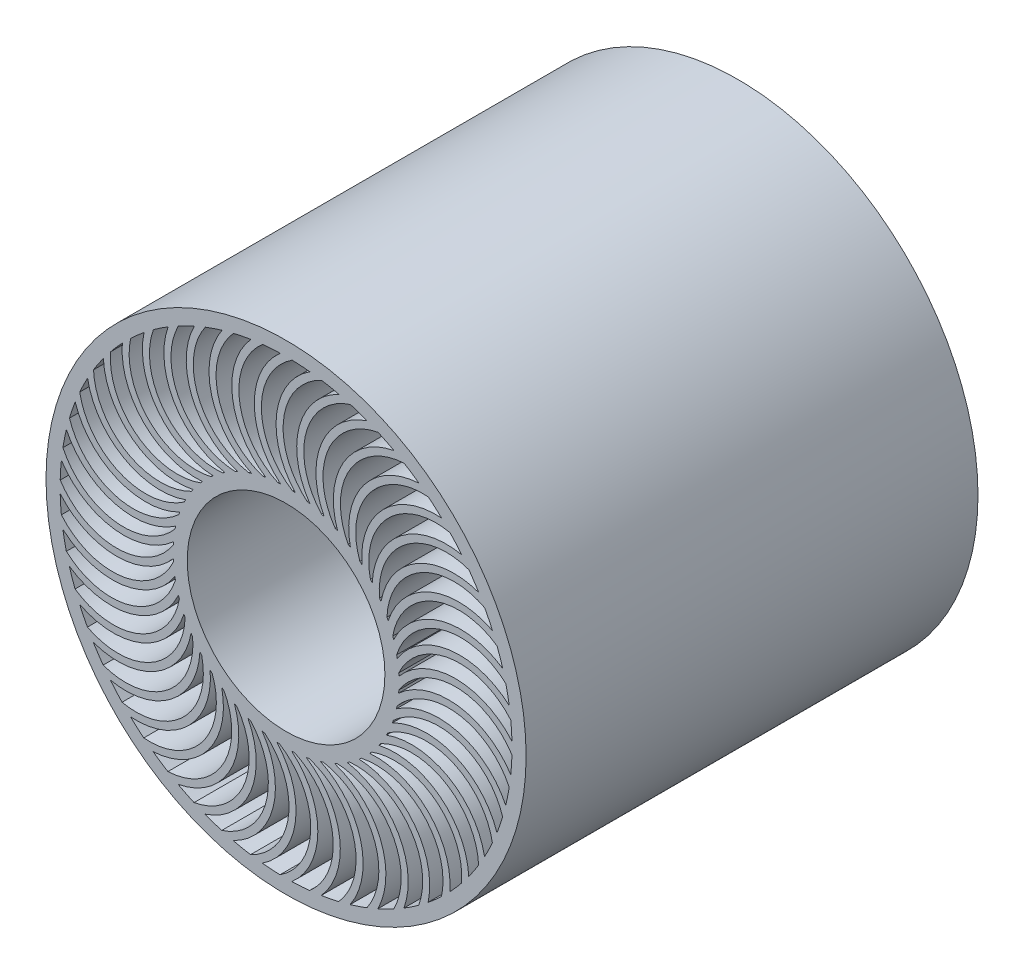
SolidWorks part; units mm, degrees
material "POLYURETHANE (11671)"
ref_plane "Front Plane" through (0, 0, 0) normal (0, 0, 1) x (1, 0, 0)
ref_plane "Top Plane" through (0, 0, 0) normal (0, 1, 0) x (1, 0, 0)
ref_plane "Right Plane" through (0, 0, 0) normal (1, 0, 0) x (0, 0, -1)
sketch "Sketch1" plane through (0, 0, 0) normal (0, 0, 1) x (1, 0, 0)
  line L0 (0, 50.8) -> (0, 101.6)
  line L1 (0, 101.6) -> (99.4973, 101.6) construction
  line L4 (1.5875, 47.8017) -> (1.5875, 104.5983) construction
  line L5 (1.5875, 101.5876) -> (1.5875, 101.6)
  line L6 (-1.5875, 54.2032) -> (-1.5875, 98.1968) construction
  circle A1 centre (0, 0) radius 107.95
  circle A2 centre (0, 0) radius 101.6
  circle A3 centre (0, 0) radius 12.7
  circle A4 centre (0, 0) radius 50.8
  arc A5 (0, 50.8) -> (0, 101.6) centre (19.0524, 76.2) cw construction
  arc A6 (-2.4712, 50.7399) -> (-2.5807, 101.5672) centre (19.0524, 76.2) cw
  arc A7 (2.914, 50.7164) -> (2.7257, 101.5634) centre (19.0524, 76.2) cw
  arc A8 (1.5875, 47.8017) -> (1.5875, 104.5983) centre (19.0524, 76.2) cw construction
  arc A9 (-1.5875, 54.2032) -> (-1.5875, 98.1968) centre (19.0524, 76.2) cw construction
  arc A10 (4.1728, 50.6283) -> (10.6986, 101.0351) centre (28.8355, 73.0613) cw
  arc A11 (9.5089, 49.9021) -> (15.9591, 100.3388) centre (28.8355, 73.0613) cw
  circle A12 centre (0, 0) radius 50.8
  arc A13 (10.7454, 49.6505) -> (23.7948, 98.7743) centre (38.1252, 68.6724) cw
  arc A14 (15.9411, 48.234) -> (28.9194, 97.3973) centre (38.1252, 68.6724) cw
  circle A15 centre (0, 0) radius 50.8
  arc A16 (17.1342, 47.8232) -> (36.4839, 94.8235) centre (46.7626, 63.1086) cw
  arc A17 (22.1005, 45.7406) -> (41.3849, 92.7893) centre (46.7626, 63.1086) cw
  circle A18 centre (0, 0) radius 50.8
  arc A19 (23.2298, 45.1776) -> (48.5487, 89.2501) centre (54.5999, 56.4649) cw
  arc A20 (27.8818, 42.4646) -> (53.1423, 86.5936) centre (54.5999, 56.4649) cw
  circle A21 centre (0, 0) radius 50.8
  arc A22 (28.9279, 41.759) -> (59.7828, 82.1497) centre (61.5029, 48.8552) cw
  arc A23 (33.186, 38.462) -> (63.9904, 78.9164) centre (61.5029, 48.8552) cw
  circle A24 centre (0, 0) radius 50.8
  arc A25 (34.1311, 37.6259) -> (69.9941, 73.6437) centre (67.3536, 40.4095) cw
  arc A26 (37.9224, 33.8013) -> (73.7436, 69.8888) centre (67.3536, 40.4095) cw
  circle A27 centre (0, 0) radius 50.8
  arc A28 (38.7503, 32.849) -> (79.0077, 63.8776) centre (72.0519, 31.2723) cw
  arc A29 (42.0099, 28.5623) -> (82.235, 59.6654) centre (72.0519, 31.2723) cw
  circle A30 centre (0, 0) radius 50.8
  arc A31 (42.7064, 27.5101) -> (86.6695, 53.0185) centre (75.5173, 21.6001) cw
  arc A32 (45.3787, 22.8346) -> (89.3194, 48.4212) centre (75.5173, 21.6001) cw
  circle A33 centre (0, 0) radius 50.8
  arc A34 (45.9318, 21.7004) -> (92.8483, 41.2523) centre (77.6907, 11.5584) cw
  arc A35 (47.971, 16.7161) -> (94.8755, 36.3484) centre (77.6907, 11.5584) cw
  circle A36 centre (0, 0) radius 50.8
  arc A37 (48.3713, 15.5195) -> (97.4385, 28.7803) centre (78.5347, 1.3188) cw
  arc A38 (49.7424, 10.3116) -> (98.8082, 23.6537) centre (78.5347, 1.3188) cw
  circle A39 centre (0, 0) radius 50.8
  arc A40 (49.9832, 9.073) -> (100.3615, 15.8158) centre (78.0349, -8.9433) cw
  arc A41 (50.6628, 3.7307) -> (101.0503, 10.5543) centre (78.0349, -8.9433) cw
  circle A42 centre (0, 0) radius 50.8
  arc A43 (50.7399, 2.4712) -> (101.5672, 2.5807) centre (76.2, -19.0524) cw
  arc A44 (50.7164, -2.914) -> (101.5634, -2.7257) centre (76.2, -19.0524) cw
  circle A45 centre (0, 0) radius 50.8
  arc A46 (50.6283, -4.1728) -> (101.0351, -10.6986) centre (73.0613, -28.8355) cw
  arc A47 (49.9021, -9.5089) -> (100.3388, -15.9591) centre (73.0613, -28.8355) cw
  circle A48 centre (0, 0) radius 50.8
  arc A49 (49.6505, -10.7454) -> (98.7743, -23.7948) centre (68.6724, -38.1252) cw
  arc A50 (48.234, -15.9411) -> (97.3973, -28.9194) centre (68.6724, -38.1252) cw
  circle A51 centre (0, 0) radius 50.8
  arc A52 (47.8232, -17.1342) -> (94.8235, -36.4839) centre (63.1086, -46.7626) cw
  arc A53 (45.7406, -22.1005) -> (92.7893, -41.3849) centre (63.1086, -46.7626) cw
  circle A54 centre (0, 0) radius 50.8
  arc A55 (45.1776, -23.2298) -> (89.2501, -48.5487) centre (56.4649, -54.5999) cw
  arc A56 (42.4646, -27.8818) -> (86.5936, -53.1423) centre (56.4649, -54.5999) cw
  circle A57 centre (0, 0) radius 50.8
  arc A58 (41.759, -28.9279) -> (82.1497, -59.7828) centre (48.8552, -61.5029) cw
  arc A59 (38.462, -33.186) -> (78.9164, -63.9904) centre (48.8552, -61.5029) cw
  circle A60 centre (0, 0) radius 50.8
  arc A61 (37.6259, -34.1311) -> (73.6437, -69.9941) centre (40.4095, -67.3536) cw
  arc A62 (33.8013, -37.9224) -> (69.8888, -73.7436) centre (40.4095, -67.3536) cw
  circle A63 centre (0, 0) radius 50.8
  arc A64 (32.849, -38.7503) -> (63.8776, -79.0077) centre (31.2723, -72.0519) cw
  arc A65 (28.5623, -42.0099) -> (59.6654, -82.235) centre (31.2723, -72.0519) cw
  circle A66 centre (0, 0) radius 50.8
  arc A67 (27.5101, -42.7064) -> (53.0185, -86.6695) centre (21.6001, -75.5173) cw
  arc A68 (22.8346, -45.3787) -> (48.4212, -89.3194) centre (21.6001, -75.5173) cw
  circle A69 centre (0, 0) radius 50.8
  arc A70 (21.7004, -45.9318) -> (41.2523, -92.8483) centre (11.5584, -77.6907) cw
  arc A71 (16.7161, -47.971) -> (36.3484, -94.8755) centre (11.5584, -77.6907) cw
  circle A72 centre (0, 0) radius 50.8
  arc A73 (15.5195, -48.3713) -> (28.7803, -97.4385) centre (1.3188, -78.5347) cw
  arc A74 (10.3116, -49.7424) -> (23.6537, -98.8082) centre (1.3188, -78.5347) cw
  circle A75 centre (0, 0) radius 50.8
  arc A76 (9.073, -49.9832) -> (15.8158, -100.3615) centre (-8.9433, -78.0349) cw
  arc A77 (3.7307, -50.6628) -> (10.5543, -101.0503) centre (-8.9433, -78.0349) cw
  circle A78 centre (0, 0) radius 50.8
  arc A79 (2.4712, -50.7399) -> (2.5807, -101.5672) centre (-19.0524, -76.2) cw
  arc A80 (-2.914, -50.7164) -> (-2.7257, -101.5634) centre (-19.0524, -76.2) cw
  circle A81 centre (0, 0) radius 50.8
  arc A82 (-4.1728, -50.6283) -> (-10.6986, -101.0351) centre (-28.8355, -73.0613) cw
  arc A83 (-9.5089, -49.9021) -> (-15.9591, -100.3388) centre (-28.8355, -73.0613) cw
  circle A84 centre (0, 0) radius 50.8
  arc A85 (-10.7454, -49.6505) -> (-23.7948, -98.7743) centre (-38.1252, -68.6724) cw
  arc A86 (-15.9411, -48.234) -> (-28.9194, -97.3973) centre (-38.1252, -68.6724) cw
  circle A87 centre (0, 0) radius 50.8
  arc A88 (-17.1342, -47.8232) -> (-36.4839, -94.8235) centre (-46.7626, -63.1086) cw
  arc A89 (-22.1005, -45.7406) -> (-41.3849, -92.7893) centre (-46.7626, -63.1086) cw
  circle A90 centre (0, 0) radius 50.8
  arc A91 (-23.2298, -45.1776) -> (-48.5487, -89.2501) centre (-54.5999, -56.4649) cw
  arc A92 (-27.8818, -42.4646) -> (-53.1423, -86.5936) centre (-54.5999, -56.4649) cw
  circle A93 centre (0, 0) radius 50.8
  arc A94 (-28.9279, -41.759) -> (-59.7828, -82.1497) centre (-61.5029, -48.8552) cw
  arc A95 (-33.186, -38.462) -> (-63.9904, -78.9164) centre (-61.5029, -48.8552) cw
  circle A96 centre (0, 0) radius 50.8
  arc A97 (-34.1311, -37.6259) -> (-69.9941, -73.6437) centre (-67.3536, -40.4095) cw
  arc A98 (-37.9224, -33.8013) -> (-73.7436, -69.8888) centre (-67.3536, -40.4095) cw
  circle A99 centre (0, 0) radius 50.8
  arc A100 (-38.7503, -32.849) -> (-79.0077, -63.8776) centre (-72.0519, -31.2723) cw
  arc A101 (-42.0099, -28.5623) -> (-82.235, -59.6654) centre (-72.0519, -31.2723) cw
  circle A102 centre (0, 0) radius 50.8
  arc A103 (-42.7064, -27.5101) -> (-86.6695, -53.0185) centre (-75.5173, -21.6001) cw
  arc A104 (-45.3787, -22.8346) -> (-89.3194, -48.4212) centre (-75.5173, -21.6001) cw
  circle A105 centre (0, 0) radius 50.8
  arc A106 (-45.9318, -21.7004) -> (-92.8483, -41.2523) centre (-77.6907, -11.5584) cw
  arc A107 (-47.971, -16.7161) -> (-94.8755, -36.3484) centre (-77.6907, -11.5584) cw
  circle A108 centre (0, 0) radius 50.8
  arc A109 (-48.3713, -15.5195) -> (-97.4385, -28.7803) centre (-78.5347, -1.3188) cw
  arc A110 (-49.7424, -10.3116) -> (-98.8082, -23.6537) centre (-78.5347, -1.3188) cw
  circle A111 centre (0, 0) radius 50.8
  arc A112 (-49.9832, -9.073) -> (-100.3615, -15.8158) centre (-78.0349, 8.9433) cw
  arc A113 (-50.6628, -3.7307) -> (-101.0503, -10.5543) centre (-78.0349, 8.9433) cw
  circle A114 centre (0, 0) radius 50.8
  arc A115 (-50.7399, -2.4712) -> (-101.5672, -2.5807) centre (-76.2, 19.0524) cw
  arc A116 (-50.7164, 2.914) -> (-101.5634, 2.7257) centre (-76.2, 19.0524) cw
  circle A117 centre (0, 0) radius 50.8
  arc A118 (-50.6283, 4.1728) -> (-101.0351, 10.6986) centre (-73.0613, 28.8355) cw
  arc A119 (-49.9021, 9.5089) -> (-100.3388, 15.9591) centre (-73.0613, 28.8355) cw
  circle A120 centre (0, 0) radius 50.8
  arc A121 (-49.6505, 10.7454) -> (-98.7743, 23.7948) centre (-68.6724, 38.1252) cw
  arc A122 (-48.234, 15.9411) -> (-97.3973, 28.9194) centre (-68.6724, 38.1252) cw
  circle A123 centre (0, 0) radius 50.8
  arc A124 (-47.8232, 17.1342) -> (-94.8235, 36.4839) centre (-63.1086, 46.7626) cw
  arc A125 (-45.7406, 22.1005) -> (-92.7893, 41.3849) centre (-63.1086, 46.7626) cw
  circle A126 centre (0, 0) radius 50.8
  arc A127 (-45.1776, 23.2298) -> (-89.2501, 48.5487) centre (-56.4649, 54.5999) cw
  arc A128 (-42.4646, 27.8818) -> (-86.5936, 53.1423) centre (-56.4649, 54.5999) cw
  circle A129 centre (0, 0) radius 50.8
  arc A130 (-41.759, 28.9279) -> (-82.1497, 59.7828) centre (-48.8552, 61.5029) cw
  arc A131 (-38.462, 33.186) -> (-78.9164, 63.9904) centre (-48.8552, 61.5029) cw
  circle A132 centre (0, 0) radius 50.8
  arc A133 (-37.6259, 34.1311) -> (-73.6437, 69.9941) centre (-40.4095, 67.3536) cw
  arc A134 (-33.8013, 37.9224) -> (-69.8888, 73.7436) centre (-40.4095, 67.3536) cw
  circle A135 centre (0, 0) radius 50.8
  arc A136 (-32.849, 38.7503) -> (-63.8776, 79.0077) centre (-31.2723, 72.0519) cw
  arc A137 (-28.5623, 42.0099) -> (-59.6654, 82.235) centre (-31.2723, 72.0519) cw
  circle A138 centre (0, 0) radius 50.8
  arc A139 (-27.5101, 42.7064) -> (-53.0185, 86.6695) centre (-21.6001, 75.5173) cw
  arc A140 (-22.8346, 45.3787) -> (-48.4212, 89.3194) centre (-21.6001, 75.5173) cw
  circle A141 centre (0, 0) radius 50.8
  arc A142 (-21.7004, 45.9318) -> (-41.2523, 92.8483) centre (-11.5584, 77.6907) cw
  arc A143 (-16.7161, 47.971) -> (-36.3484, 94.8755) centre (-11.5584, 77.6907) cw
  circle A144 centre (0, 0) radius 50.8
  arc A145 (-15.5195, 48.3713) -> (-28.7803, 97.4385) centre (-1.3188, 78.5347) cw
  arc A146 (-10.3116, 49.7424) -> (-23.6537, 98.8082) centre (-1.3188, 78.5347) cw
  circle A147 centre (0, 0) radius 50.8
  arc A148 (-9.073, 49.9832) -> (-15.8158, 100.3615) centre (8.9433, 78.0349) cw
  arc A149 (-3.7307, 50.6628) -> (-10.5543, 101.0503) centre (8.9433, 78.0349) cw
  circle A150 centre (0, 0) radius 50.8
  circle A151 centre (0, 0) radius 44.45
  point P158 (0, 0)
  point P355 (0, 0)
  dimension "D1" = 1.5875
  dimension "D2" = 215.9
  dimension "D3" = 203.2
  dimension "D4" = 25.4
  dimension "D5" = 101.6
  dimension "D8" = 88.9
  dimension "D6" = 1.5875
  dimension "D7" = 48
extrude "Boss-Extrude1" add sketch "Sketch1" along normal blind 203.2
